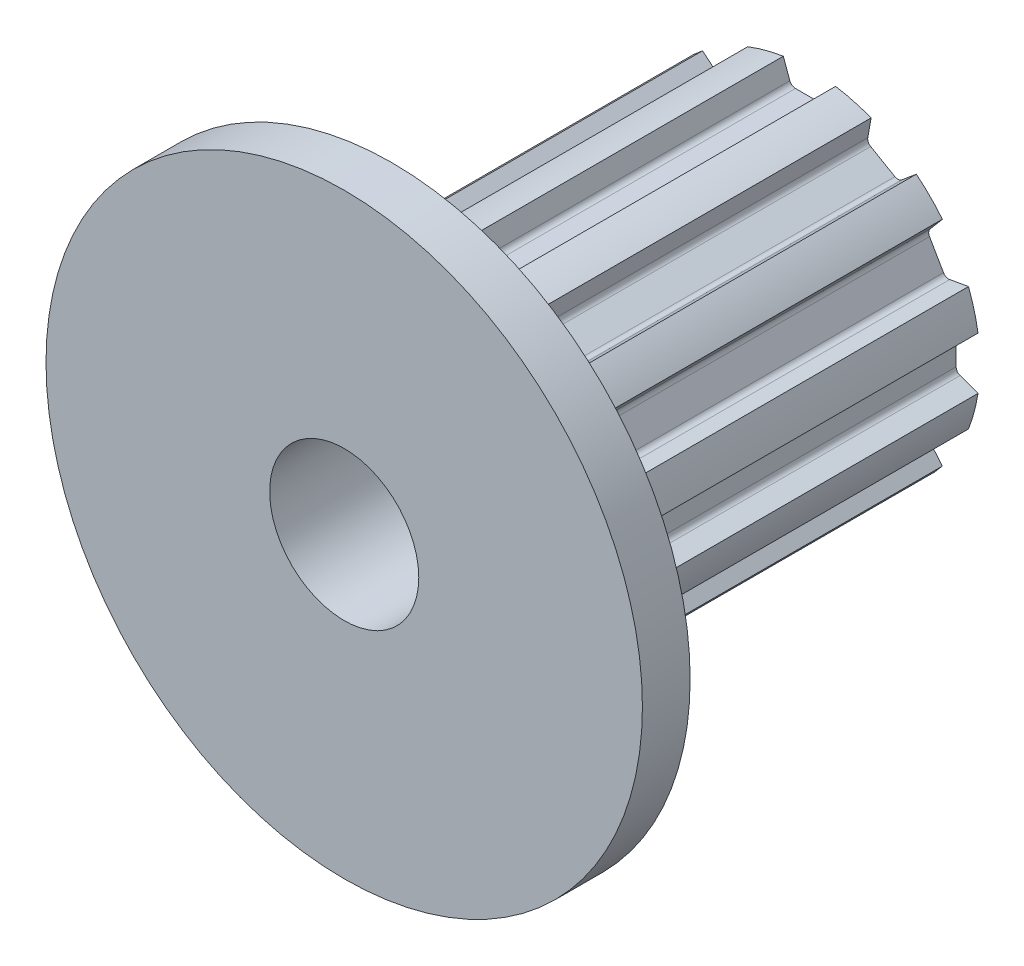
SolidWorks part; units mm, degrees
extrude "BasePulley" add sketch "Sketch1" against normal blind 8.89
sketch "Sketch1" plane through (0, 0, 0) normal (0, 0, 1) x (1, 0, 0)
  circle A0 centre (0, 0) radius 3.6322
  dimension "Outside_dia" = 7.2644
revolve "Flange" [suppressed] add sketch "Sketch2" angle 360 about L11
sketch "Sketch2" plane through (0, 0, 0) normal (1, 0, 0) x (0, 0, -1)
  line L0 (8.89, 3.6322) -> (9.0453, 4.1402)
  line L1 (9.0453, 4.1402) -> (9.604, 3.9694)
  line L2 (4.445, 0) -> (4.445, 66.675) construction
  line L3 (9.604, 3.9694) -> (9.4742, 3.5449)
  line L4 (9.4742, 3.5449) -> (9.4742, 0)
  line L5 (0, 3.6322) -> (-0.1553, 4.1402)
  line L6 (8.89, -3.6322) -> (8.89, 3.6322) construction
  line L7 (-0.1553, 4.1402) -> (-0.714, 3.9694)
  line L8 (-0.714, 3.9694) -> (-0.5842, 3.5449)
  line L9 (-0.5842, 3.5449) -> (-0.5842, 0)
  line L10 (8.89, 3.6322) -> (0, 3.6322)
  line L11 (0, 0) -> (38.2092, 0) construction
  line L12 (8.89, 0) -> (0, 0) construction
  line L13 (-0.5842, 0) -> (9.4742, 0)
  dimension "D1" = 4.445
  dimension "Flange_ang" = 17
  dimension "D3" = 0.5842
  dimension "D2" = 3.6322
  dimension "Flange_ht" = 0.508
ref_plane "Plane1" through (0, 0, 0) normal (0, 0, 1) x (1, 0, 0)
ref_plane "Plane2" through (0, 0, 0) normal (0, 1, 0) x (1, 0, 0)
ref_plane "Plane3" through (0, 0, 0) normal (1, 0, 0) x (0, 0, -1)
sketch "Clipboard" plane through (0, 0, 0) normal (0, 0, 1) x (1, 0, 0)
  line L0 (0, 0) -> (3.429, 0)
  line L1 (0, 0) -> (7.7019, 1.6371)
  line L2 (0, 0) -> (7.7019, -1.6371)
ref_plane "Plane4" through (0, 0, -4.445) normal (0, 0, 1) x (1, 0, 0)
sketch "Sketch3" plane through (0, 0, -4.445) normal (0, 0, 1) x (1, 0, 0)
  line L0 (-0.5715, 3.6322) -> (-0.5715, 29.0322)
  line L1 (0.5715, 3.6322) -> (0.5715, 29.0322)
  line L2 (0, 0) -> (0, 3.6322) construction
  line L3 (-0.5715, 3.6322) -> (0.5715, 3.6322) construction
  line L4 (-0.2977, 3.1242) -> (0.2977, 3.1242)
  line L5 (0.5715, 3.6322) -> (0.417, 3.2078)
  line L6 (-0.5715, 3.6322) -> (-0.417, 3.2078)
  line L7 (0.5715, 29.0322) -> (-0.5715, 29.0322)
  arc A0 (0.2977, 3.1242) -> (0.417, 3.2078) centre (0.2977, 3.2512) ccw
  arc A2 (-0.417, 3.2078) -> (-0.2977, 3.1242) centre (-0.2977, 3.2512) ccw
  dimension "Grv_rad_bot" = 0.127
  dimension "Grv_ang" = 40
  dimension "D3" = 20
  dimension "Grv_width" = 1.143
  dimension "D4" = 25.4
  dimension "D1" = 3.6322
  dimension "Grv_depth" = 0.508
extrude "Groove" cut sketch "Sketch3" against normal mid plane 8.89
pattern_circular "Grooves" count 12 every 30 about axis through (0, 0, -8.89) along (0, 0, 1) of "Groove"
sketch "Sketch4" plane through (0, 0, 0) normal (1, 0, 0) x (0, 0, -1)
  line L0 (0, 0) -> (47.6781, 0) construction
  line L1 (8.89, 0) -> (0, 0) construction
  line L2 (0, 0) -> (-1.016, 0)
  line L3 (-1.016, 0) -> (-1.016, 6.35)
  line L4 (-1.016, 6.35) -> (0, 6.35)
  line L5 (0, 6.35) -> (0, 0)
  line L6 (-1.016, -6.35) -> (0, -6.35) construction
revolve "BaseHub" add sketch "Sketch4" angle 360 about L0
sketch "BorSke" plane through (0, 0, 1.016) normal (0, 0, 1) x (1, 0, 0)
  circle A0 centre (0, 0) radius 1.5875
extrude "Bore" cut sketch "BorSke" against normal through all
sketch "KeySke" plane through (0, 0, 1.016) normal (0, 0, 1) x (1, 0, 0)
  line L0 (0.127, 1.8415) -> (0.127, 0)
  line L1 (0.127, 1.8415) -> (-0.127, 1.8415)
  line L2 (-0.127, 1.8415) -> (-0.127, 0)
  line L3 (-0.127, 0) -> (0.127, 0)
  line L4 (0, 31.75) -> (0, -3.175) construction
  dimension "Width" = 8.89
extrude "Keyway" [suppressed] cut sketch "KeySke" against normal through all
pattern_circular "Keyway2" [suppressed] count 2 every 90
equation "\"D1@Plane4\" = \"Width@BasePulley\" / 2"
equation "\"D1@Groove\" = \"Width@BasePulley\""
equation "\"D1@Sketch3\" = \"Outside_dia@Sketch1\" / 2"
equation "\"D1@Sketch2\" = \"Width@BasePulley\" / 2"
equation "\"D2@Sketch2\" = \"Outside_dia@Sketch1\" / 2"
equation "\"D3@Sketch2\" = \"Flange_thickness@Sketch2\""
equation "\"Num_grvs@Clipboard\" = int( \"Num_grvs@Clipboard\" )"
equation "\"Show_grvs@Clipboard\" = int( \"Show_grvs@Clipboard\" )"
equation "\"Show_grvs@Clipboard\" = ((sgn( \"Show_grvs@Clipboard\" - \"Num_grvs@Clipboard\" )-1)*( \"Show_grvs@Clipboard\" - \"Num_grvs@Clipboard\" ))/-2+ \"Num_grvs@Clipboard\""
equation "\"Show_grvs@Clipboard\" = ((sgn( \"Show_grvs@Clipboard\" - 1.0)+1)*( \"Show_grvs@Clipboard\" - 1.0))/2 +1.0"
equation "\"Angle@Grooves\" = 360.0 / \"Num_grvs@Clipboard\""
equation "\"Num_grvs@Grooves\" =  \"Show_grvs@Clipboard\""
equation "\"Offset@KeySke\" = \"T_dim@Clipboard\" - \"Diameter@BorSke\" / 2.0"
equation "\"OAL@Clipboard\" = \"Overall_len@Clipboard\""
equation "\"Hub_depth@Sketch4\" = \"OAL@Clipboard\" - \"Width@BasePulley\""
